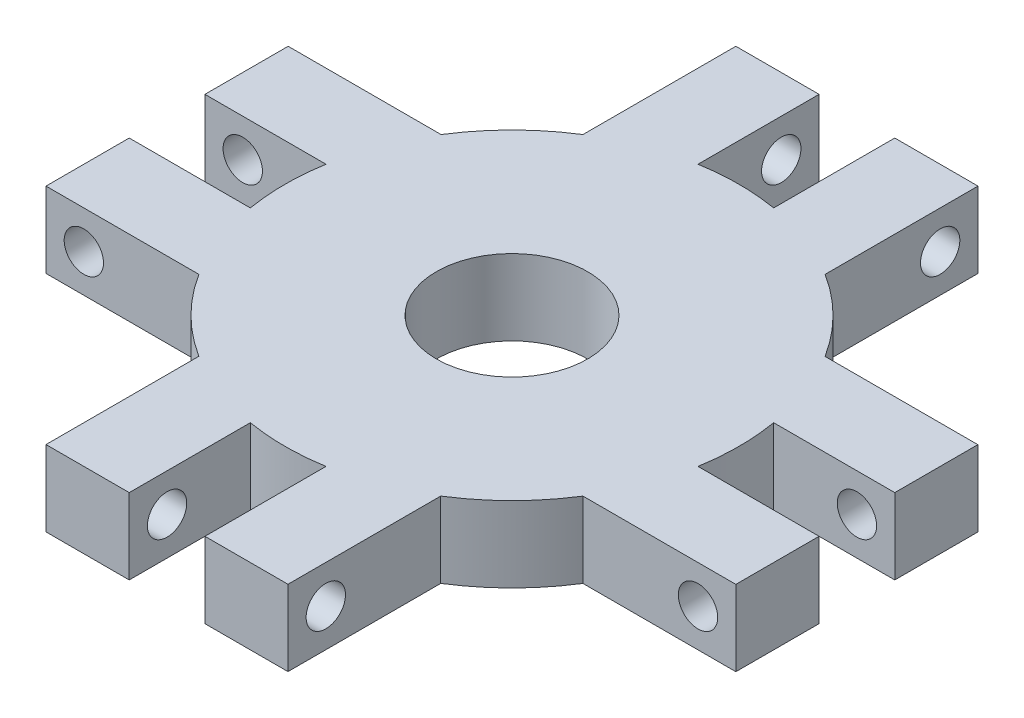
SolidWorks part; units mm, degrees
ref_plane "Front Plane" through (0, 0, 0) normal (0, 0, 1) x (1, 0, 0)
ref_plane "Top Plane" through (0, 0, 0) normal (0, 1, 0) x (1, 0, 0)
ref_plane "Right Plane" through (0, 0, 0) normal (1, 0, 0) x (0, 0, -1)
sketch "Sketch1" plane through (0, 0, 0) normal (0, 1, 0) x (1, 0, 0)
  line L0 (0, 19.05) -> (0, -19.05) construction
  line L1 (10.16, 19.05) -> (-10.16, 19.05) construction
  line L2 (3.175, 19.05) -> (-3.175, 19.05) construction
  line L3 (-3.175, 28.9436) -> (-10.16, 28.9436)
  line L4 (-3.175, 18.7836) -> (-3.175, 28.9436)
  line L5 (-10.16, 28.9436) -> (-10.16, 16.1145)
  line L6 (3.175, 18.7836) -> (3.175, 28.9436)
  line L7 (3.175, 28.9436) -> (10.16, 28.9436)
  line L8 (10.16, 28.9436) -> (10.16, 16.1145)
  line L9 (10.16, -19.05) -> (-10.16, -19.05) construction
  line L10 (3.175, -19.05) -> (-3.175, -19.05) construction
  line L11 (-3.175, -18.7836) -> (-3.175, -28.9436)
  line L12 (3.175, -18.7836) -> (3.175, -28.9436)
  line L13 (-3.175, -28.9436) -> (-10.16, -28.9436)
  line L14 (3.175, -28.9436) -> (10.1443, -28.9436)
  line L15 (-10.16, -28.9436) -> (-10.16, -16.1145)
  line L16 (10.1443, -28.9436) -> (10.1443, -16.1244)
  line L17 (-19.05, 0) -> (19.05, 0) construction
  line L18 (-19.05, 10.16) -> (-19.05, -10.16) construction
  line L19 (-19.05, 3.175) -> (-19.05, -3.175) construction
  line L20 (-18.7836, -3.175) -> (-28.9436, -3.175)
  line L21 (-18.7836, 3.175) -> (-28.9436, 3.175)
  line L22 (-28.9436, 3.175) -> (-28.9436, 10.16)
  line L23 (-28.9436, -3.175) -> (-28.9436, -10.16)
  line L24 (-28.9436, -10.16) -> (-16.1145, -10.16)
  line L25 (-28.9436, 10.16) -> (-16.1145, 10.16)
  line L26 (19.05, 10.16) -> (19.05, -10.16) construction
  line L27 (19.05, -3.175) -> (19.05, 3.175) construction
  line L28 (18.7836, 3.175) -> (28.9436, 3.175)
  line L29 (18.7836, -3.175) -> (28.9436, -3.175)
  line L30 (28.9436, -3.175) -> (28.9436, -10.16)
  line L31 (28.9436, 3.175) -> (28.9436, 10.1466)
  line L32 (28.9436, 10.1466) -> (16.1229, 10.1466)
  line L33 (28.9436, -10.16) -> (16.1145, -10.16)
  circle A0 centre (0, 0) radius 19.05
  point P7 (0, 19.05)
  point P8 (0, 19.05)
  point P10 (0, 19.05)
  point P14 (0, 19.05)
  point P24 (0, -19.05)
  point P26 (0, -19.05)
  point P40 (-19.05, 0)
  point P42 (-19.05, 0)
  point P54 (19.05, 0)
  point P56 (19.05, 0)
extrude "Boss-Extrude1" add sketch "Sketch1" along normal blind 6.35 contours A0 L4 L3 L5 | A0 L8 L7 L6 | A0 L25 L22 L21 | A0 L20 L23 L24 | A0 L15 L13 L11 | A0 L12 L14 L16 | A0 L33 L30 L29 | A0 L28 L31 L32
sketch "Sketch2" plane through (10.16, 0, 0) normal (1, 0, 0) x (0, 0, -1)
  line L0 (28.9436, 3.175) -> (25.7686, 3.175) construction
  line L1 (28.9436, 6.35) -> (28.9436, 0) construction
  circle A0 centre (25.7686, 3.175) radius 1.651
extrude "Cut-Extrude1" cut sketch "Sketch2" against normal blind 23.368
sketch "Sketch3" plane through (0, 0, -10.1466) normal (0, 0, -1) x (-1, 0, 0)
  line L0 (-28.9436, 3.175) -> (-25.7686, 3.175) construction
  line L1 (-28.9436, 6.35) -> (-28.9436, 0) construction
  circle A0 centre (-25.7686, 3.175) radius 1.651
extrude "Cut-Extrude2" cut sketch "Sketch3" against normal blind 23.368
sketch "Sketch4" plane through (10.1443, 0, 0) normal (1, 0, 0) x (0, 0, -1)
  line L0 (-28.9436, 3.175) -> (-25.7686, 3.175) construction
  line L1 (-28.9436, 6.35) -> (-28.9436, 0) construction
  circle A0 centre (-25.7686, 3.175) radius 1.651
extrude "Cut-Extrude3" cut sketch "Sketch4" against normal blind 23.368
sketch "Sketch5" plane through (0, 0, 10.16) normal (0, 0, 1) x (1, 0, 0)
  line L0 (-28.9436, 3.175) -> (-25.7686, 3.175) construction
  line L1 (-28.9436, 6.35) -> (-28.9436, 0) construction
  circle A0 centre (-25.7686, 3.175) radius 1.651
extrude "Cut-Extrude4" cut sketch "Sketch5" against normal blind 23.368
sketch "Sketch6" plane through (0, 6.35, 0) normal (0, 1, 0) x (1, 0, 0)
  circle A0 centre (0, 0) radius 6.35
extrude "Cut-Extrude5" cut sketch "Sketch6" against normal blind 14.3002
